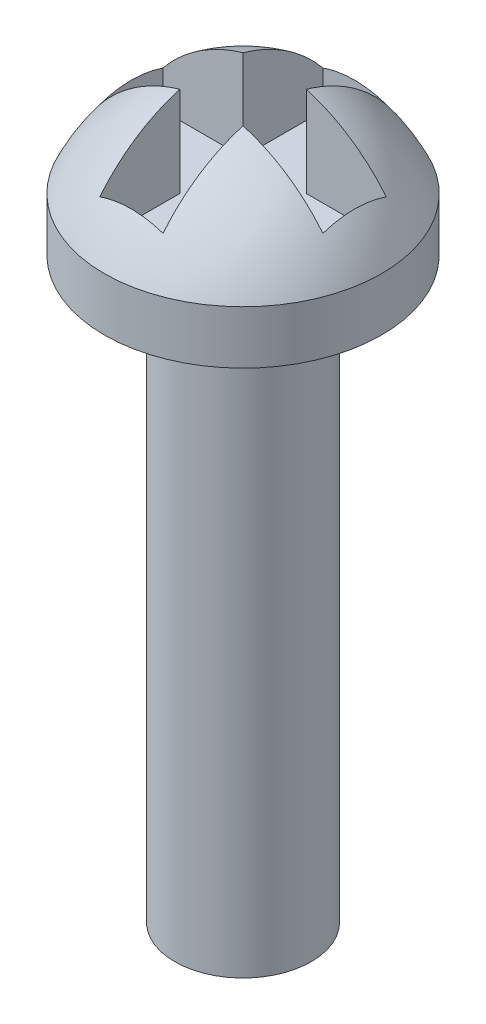
SolidWorks part; units mm, degrees
ref_plane "Front Plane" through (0, 0, 0) normal (0, 0, 1) x (1, 0, 0)
ref_plane "Top Plane" through (0, 0, 0) normal (0, 1, 0) x (1, 0, 0)
ref_plane "Right Plane" through (0, 0, 0) normal (1, 0, 0) x (0, 0, -1)
sketch "Sketch1" plane through (0, 0, 0) normal (0, 0, 1) x (1, 0, 0)
  line L0 (0, 0) -> (0, 12.7)
  line L1 (0, 18.8812) -> (0, -9.93) construction
  line L2 (1.5, 12.7) -> (1.5, 0)
  line L3 (1.5, 0) -> (0, 0)
  line L4 (0, 12.7) -> (0, 13.8684)
  line L6 (3.048, 13.8684) -> (3.048, 12.7)
  line L7 (3.048, 12.7) -> (1.5, 12.7)
  line L8 (0, 13.8684) -> (0, 16.1284)
  spline S0 degree 2 poles (0, 16.1284) (2.1581, 15.7489) (3.048, 13.8684) knots 0 0 0 1 1 1
  dimension "D1" = 12.7
  dimension "D2" = 1.5
  dimension "D3" = 1.1684
  dimension "D4" = 3.048
revolve "Revolve1" add sketch "Sketch1" angle 360 about L1
ref_plane "Plane1" through (0, 13.8684, 0) normal (0, -1, 0) x (-1, 0, 0)
sketch "Sketch2" plane through (0, 13.8684, 0) normal (0, -1, 0) x (-1, 0, 0)
  line L1 (2.4522, -0.6951) -> (-2.4522, -0.6951)
  line L2 (2.4522, -0.6951) -> (2.4522, 0.6951)
  line L3 (2.4522, 0.6951) -> (-2.4522, 0.6951)
  line L4 (-2.4522, -0.6951) -> (-2.4522, 0.6951)
  line L5 (2.4522, -0.6951) -> (-2.4522, 0.6951) construction
  line L6 (2.4522, 0.6951) -> (-2.4522, -0.6951) construction
  line L7 (0.6951, -2.4522) -> (-0.6951, -2.4522)
  line L8 (0.6951, -2.4522) -> (0.6951, 2.4522)
  line L9 (0.6951, 2.4522) -> (-0.6951, 2.4522)
  line L10 (-0.6951, -2.4522) -> (-0.6951, 2.4522)
  line L11 (0.6951, -2.4522) -> (-0.6951, 2.4522) construction
  line L12 (0.6951, 2.4522) -> (-0.6951, -2.4522) construction
  point P0 (0, 0)
  point P6 (0, 0)
extrude "Cut-Extrude1" cut sketch "Sketch2" against normal up to next contours L1 L4 L3 L2 | L10 L9 L8 L7
